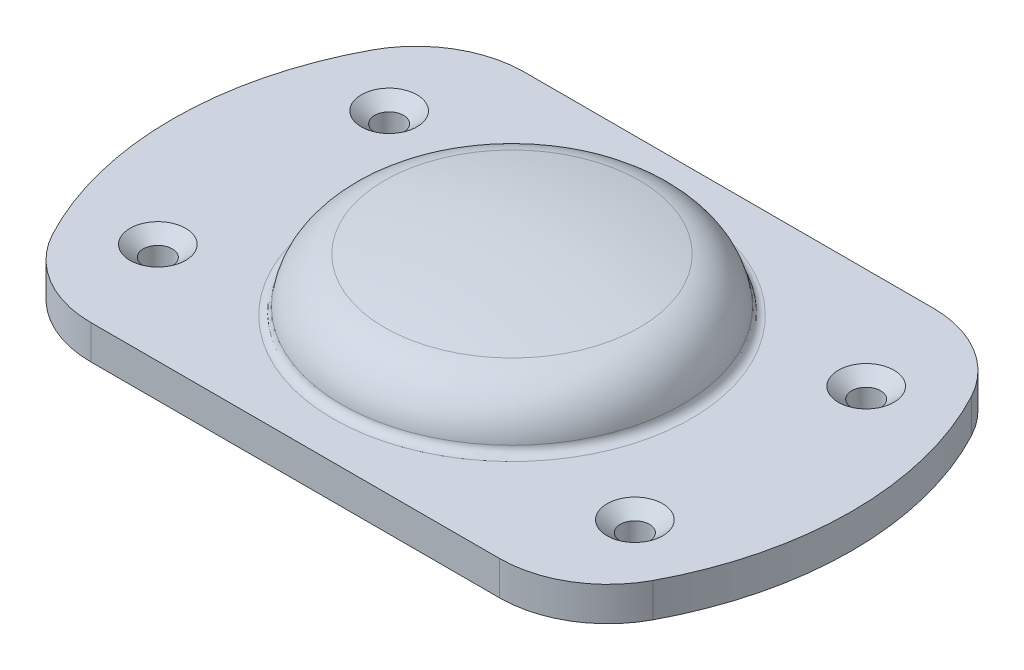
SolidWorks part; units mm, degrees
ref_plane "Front Plane" through (0, 0, 0) normal (0, 0, 1) x (1, 0, 0)
ref_plane "Top Plane" through (0, 0, 0) normal (0, 1, 0) x (1, 0, 0)
ref_plane "Right Plane" through (0, 0, 0) normal (1, 0, 0) x (0, 0, -1)
sketch "Sketch1" plane through (0, 0, 0) normal (0, 1, 0) x (1, 0, 0)
  line L0 (-59.69, 0) -> (0, 0) construction
  line L1 (-59.69, 38.1) -> (59.69, 38.1) construction
  line L2 (-59.69, 38.1) -> (-59.69, -38.1) construction
  line L3 (-59.69, -38.1) -> (59.69, -38.1) construction
  line L4 (59.69, 38.1) -> (59.69, -38.1) construction
  line L5 (-59.69, 38.1) -> (59.69, -38.1) construction
  line L6 (-59.69, -38.1) -> (59.69, 38.1) construction
  line L7 (-41.91, 20.32) -> (41.91, 20.32) construction
  line L8 (-41.91, 20.32) -> (-41.91, -20.32) construction
  line L9 (-41.91, -20.32) -> (41.91, -20.32) construction
  line L10 (41.91, 20.32) -> (41.91, -20.32) construction
  line L11 (0, 0) -> (0, 38.1) construction
  line L12 (-35.8986, -38.1) -> (35.8986, -38.1)
  line L13 (-35.8986, 38.1) -> (35.8986, 38.1)
  arc A0 (-52.726, -27.9797) -> (-52.726, 27.9797) centre (0, 0) cw
  arc A1 (-52.726, 27.9797) -> (-35.8986, 38.1) centre (-35.8986, 19.05) cw
  arc A2 (-52.726, -27.9797) -> (-35.8986, -38.1) centre (-35.8986, -19.05) ccw
  arc A3 (52.726, -27.9797) -> (35.8986, -38.1) centre (35.8986, -19.05) cw
  arc A4 (52.726, 27.9797) -> (35.8986, 38.1) centre (35.8986, 19.05) ccw
  arc A5 (52.726, -27.9797) -> (52.726, 27.9797) centre (0, 0) ccw
  point P0 (0, 0)
  point P9 (-41.91, 20.32)
  dimension "D7" = 59.69
  dimension "D8" = 19.05
  dimension "D1" = 76.2
  dimension "D2" = 119.38
  dimension "D3" = 20.32
  dimension "D4" = 41.91
  dimension "D5" = 41.91
  dimension "D6" = 20.32
extrude "Boss-Extrude1" add sketch "Sketch1" along normal blind 5.9944
sketch "Sketch3" plane through (0, 0, 0) normal (0, 0, 1) x (1, 0, 0)
  line L0 (0, 0) -> (0, 17.6022) construction
  line L1 (0, 17.6022) -> (18.6521, 17.6022) construction
  line L2 (0, 0) -> (-29.9974, 0) construction
  line L3 (-29.9974, 0) -> (-29.9974, 5.9944) construction
  line L4 (-35.8986, 5.9944) -> (35.8986, 5.9944) construction
  line L5 (-29.9974, 5.9944) -> (0, 5.9944)
  line L6 (0, 17.6022) -> (0, 5.9944)
  arc A0 (0, 17.6022) -> (-22.3906, 15.3242) centre (0, -93.5786) ccw
  arc A1 (-22.3906, 15.3242) -> (-29.9974, 5.9944) centre (-20.4724, 5.9944) ccw
  dimension "D3" = 9.525
  dimension "D1" = 17.6022
  dimension "D2" = 29.9974
revolve "Revolve1" add sketch "Sketch3" angle 360 about L6
fillet "Fillet1" radius 1.5875 1 edges at (-29.9974, 5.9944, 0)
sketch "Sketch4" plane through (0, 5.9944, 0) normal (0, 1, 0) x (1, 0, 0)
  point P0 (-41.91, 20.32)
  point P2 (-41.91, -20.32)
  point P4 (41.91, -20.32)
  point P6 (41.91, 20.32)
hole_wizard "CSK for #10 Flat Head Machine Screw (100)1" positions "Sketch6" profile "Sketch5" countersink size "#10" standard "Ansi Inch" end condition through all
sketch "Sketch6" plane through (0, 5.9944, 0) normal (0, 1, 0) x (-1, 0, 0)
  point P0 (41.91, -20.32)
  point P1 (41.91, 20.32)
  point P3 (-41.91, -20.32)
  point P5 (-41.91, 20.32)
sketch "Sketch5" plane through (-41.91, 5.9944, -20.32) normal (1, 0, 0) x (0, 0, 1)
  line L0 (0, 0) -> (0, 5.9944)
  line L1 (0, 5.9944) -> (2.5527, 5.9944)
  line L2 (2.5527, 5.9944) -> (2.5527, 1.9608)
  line L3 (2.5527, 1.9608) -> (4.8895, 0)
  line L5 (4.8895, 0) -> (0, 0)
  line L6 (-2.5527, 1.9608) -> (-4.8895, 0) construction
  line L11 (0, -6.35) -> (0, 107.95) construction
  dimension "Thru Hole Dia." = 5.1054
  dimension "Thru Hole Depth" = 5.9944
  dimension "Near C'Sink Dia." = 9.779
  dimension "Near C'Sink Angle" = 100
